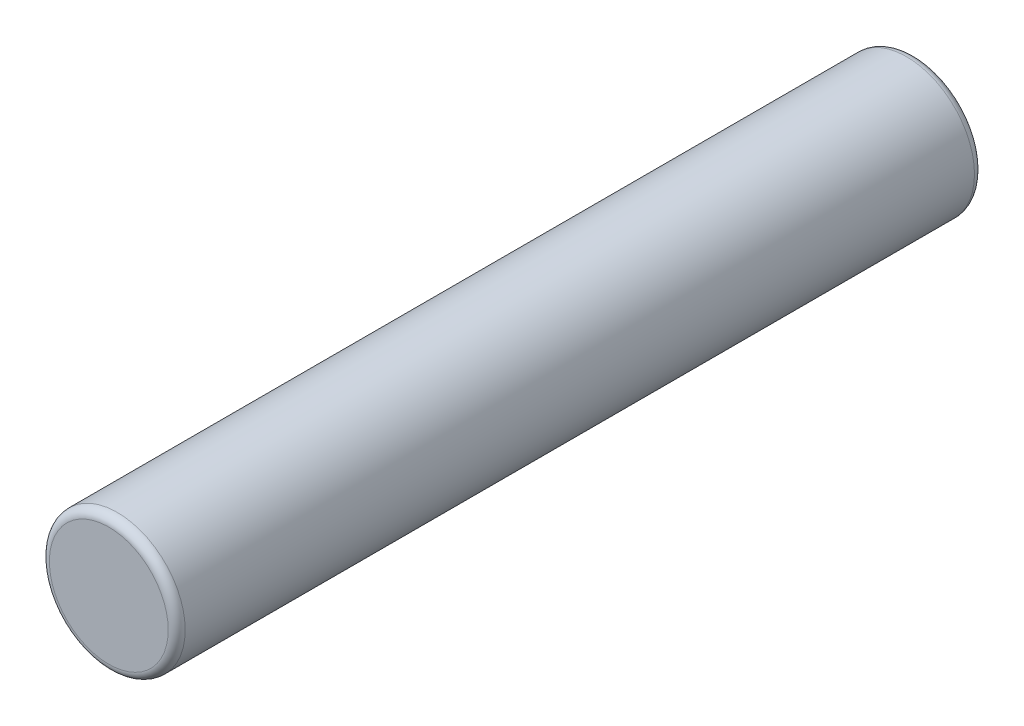
SolidWorks part; units mm, degrees
ref_plane "Front Plane" through (0, 0, 0) normal (0, 0, 1) x (1, 0, 0)
ref_plane "Top Plane" through (0, 0, 0) normal (0, 1, 0) x (1, 0, 0)
ref_plane "Right Plane" through (0, 0, 0) normal (1, 0, 0) x (0, 0, -1)
sketch "Sketch2" plane through (0, 0, 0) normal (0, 0, 1) x (1, 0, 0)
  circle A0 centre (-1.6912, 0.3412) radius 0.8
  dimension "D1" = 1.6
extrude "Boss-Extrude1" add sketch "Sketch2" along normal blind 9.5
fillet "Fillet1" radius 0.1 2 edges at (-0.8912, 0.3412, 0) (-0.8912, 0.3412, 9.5)
